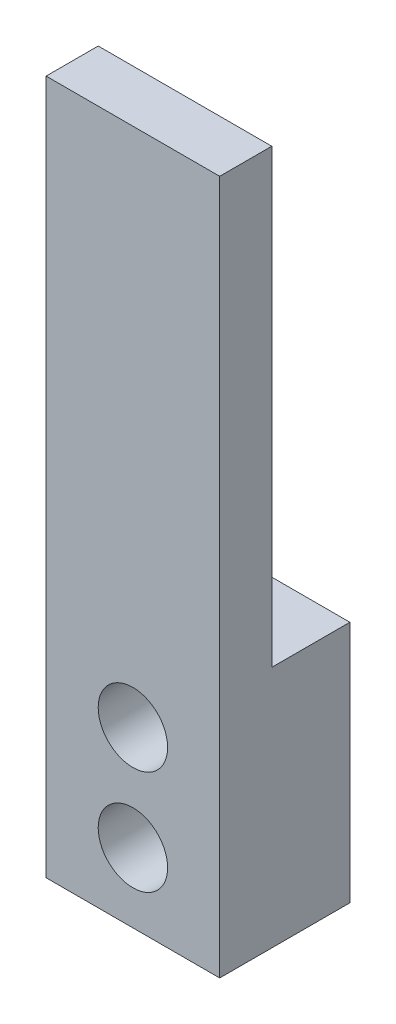
SolidWorks part; units mm, degrees
ref_plane "Front" through (0, 0, 0) normal (0, 0, 1) x (1, 0, 0)
ref_plane "Top" through (0, 0, 0) normal (0, 1, 0) x (1, 0, 0)
ref_plane "Right" through (0, 0, 0) normal (1, 0, 0) x (0, 0, -1)
sketch "Sketch2" plane through (0, 0, 0) normal (0, 0, 1) x (1, 0, 0)
  line L1 (-2.5, 0) -> (2.5, 0)
  line L2 (-2.5, 0) -> (-2.5, -20)
  line L3 (-2.5, -20) -> (2.5, -20)
  line L4 (2.5, 0) -> (2.5, -20)
  dimension "D2" = 2.5
  dimension "D3" = 20
extrude "Extrude1" add sketch "Sketch2" along normal blind 3.75
sketch "Sketch3" plane through (0, 0, 0) normal (0, 0, -1) x (-1, 0, 0)
  line L0 (2.5, 0) -> (2.5, -20) construction
  line L1 (-2.5, 0) -> (2.5, 0)
  line L2 (-2.5, 0) -> (-2.5, -13)
  line L3 (-2.5, -13) -> (2.5, -13)
  line L4 (2.5, 0) -> (2.5, -13)
  line L5 (2.5, -20) -> (-2.5, -20) construction
  dimension "D1" = 7
extrude "Extrude2" cut sketch "Sketch3" against normal blind 2.25
sketch "Sketch4" plane through (0, 0, 0) normal (0, 0, -1) x (-1, 0, 0)
  line L0 (2.5, -13) -> (2.5, -20) construction
  line L2 (-2.5, -13) -> (2.5, -13) construction
  circle A0 centre (0, -18) radius 1
  circle A1 centre (0, -15) radius 1
  dimension "D1" = 2
  dimension "D2" = 2
  dimension "D6" = 2
  dimension "D3" = 2.5
  dimension "D4" = 2.5
  dimension "D5" = 3
extrude "Extrude3" cut sketch "Sketch4" against normal up to surface (3.75 mm away) up to face at (0, -10, 3.75)
